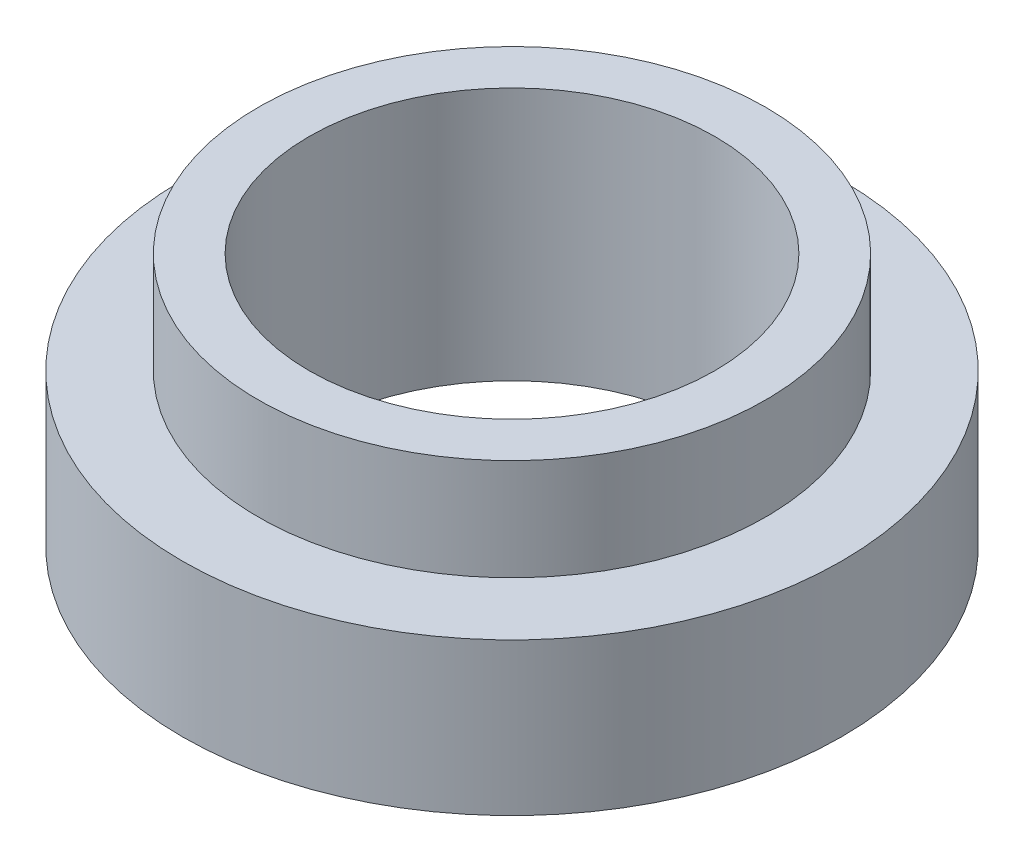
SolidWorks part; units mm, degrees
ref_plane "Piano frontale" through (0, 0, 0) normal (0, 0, 1) x (1, 0, 0)
ref_plane "Piano superiore" through (0, 0, 0) normal (0, 1, 0) x (1, 0, 0)
ref_plane "Piano destro" through (0, 0, 0) normal (1, 0, 0) x (0, 0, -1)
sketch "Schizzo1" plane through (0, 0, 0) normal (0, 0, 1) x (1, 0, 0)
  line L0 (0, 0) -> (0, 28.3713) construction
  line L1 (-6.5, 14.3178) -> (-4, 14.3178)
  line L2 (-6.5, 14.3178) -> (-6.5, 17.3178)
  line L3 (-6.5, 17.3178) -> (-5, 17.3178)
  line L4 (-5, 17.3178) -> (-5, 19.3178)
  line L5 (-5, 19.3178) -> (-4, 19.3178)
  line L6 (-4, 19.3178) -> (-4, 14.3178)
  dimension "D1" = 13
  dimension "D2" = 3
  dimension "D3" = 10
  dimension "D4" = 8
  dimension "D5" = 5
revolve "Rivoluzione1" add sketch "Schizzo1" angle 360 about L0
